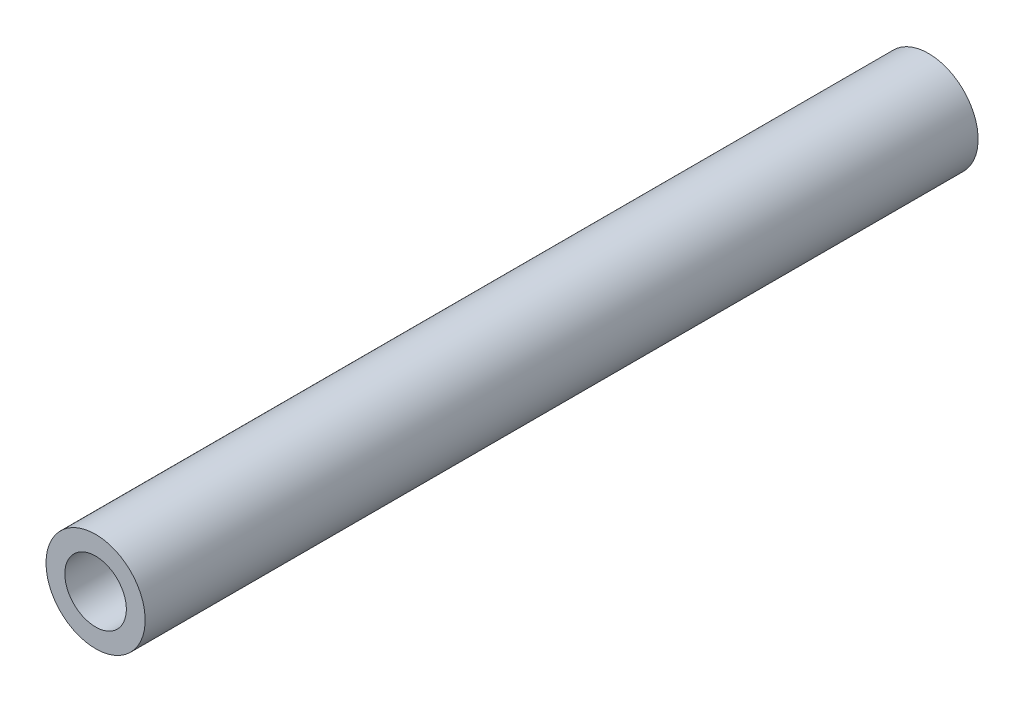
SolidWorks part; units mm, degrees
material "7050-T73510"
ref_plane "前视基准面" through (0, 0, 0) normal (0, 0, 1) x (1, 0, 0)
ref_plane "上视基准面" through (0, 0, 0) normal (0, 1, 0) x (1, 0, 0)
ref_plane "右视基准面" through (0, 0, 0) normal (1, 0, 0) x (0, 0, -1)
sketch "草图1" plane through (0, 0, 0) normal (0, 0, 1) x (1, 0, 0)
  circle A0 centre (0, 0) radius 2.5
  circle A1 centre (0, 0) radius 1.55
  dimension "D1" = 3.1
  dimension "D2" = 5
extrude "凸台-拉伸1" add sketch "草图1" along normal blind 42
